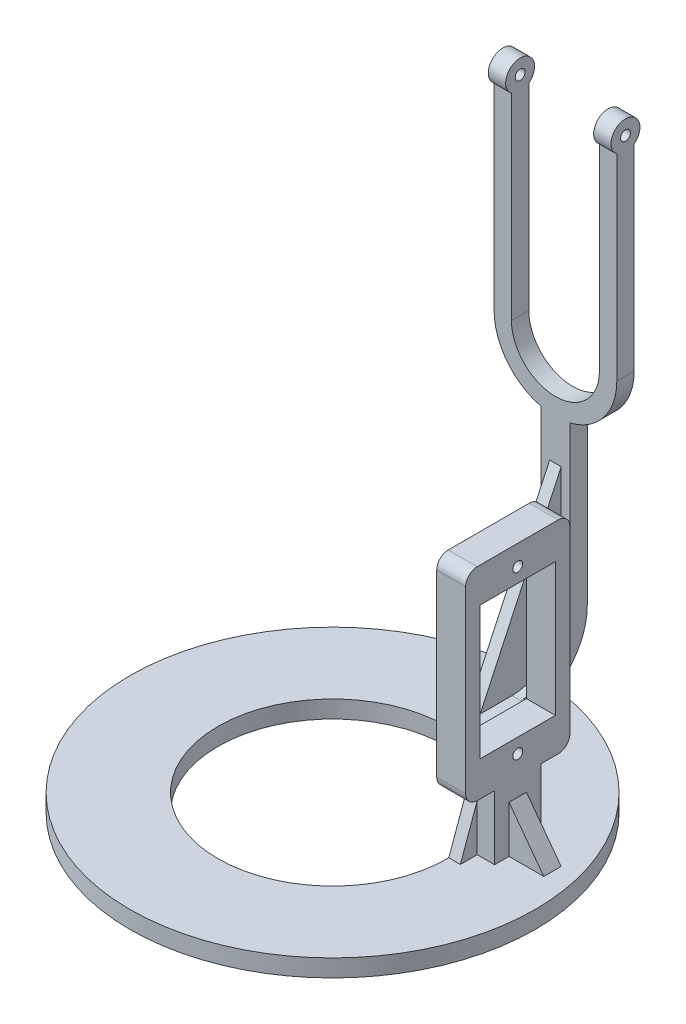
SolidWorks part; units mm, degrees
ref_plane "Plano frontal" through (0, 0, 0) normal (0, 0, 1) x (1, 0, 0)
ref_plane "Plano superior" through (0, 0, 0) normal (0, 1, 0) x (1, 0, 0)
ref_plane "Plano direito" through (0, 0, 0) normal (1, 0, 0) x (0, 0, -1)
ref_plane "Plano1" through (19.8, 0, 0) normal (1, 0, 0) x (0, 0, -1)
sketch "Esboço1" plane through (0, 0, 0) normal (1, 0, 0) x (0, 0, -1)
  circle A0 centre (0, 0) radius 2.5
  dimension "D1" = 5
extrude "Ressalto-extrusão1" add sketch "Esboço1" along normal mid plane 21.2
sketch "Esboço8" plane through (0, 0, 0) normal (0, 0, 1) x (1, 0, 0)
  line L0 (10.6, -2.5) -> (10.6, 2.5) construction
  line L1 (-10.6, 0) -> (10.6, 0)
  line L2 (-10.6, 0) -> (-10.6, -35)
  line L3 (-10.6, -35) -> (10.6, -35)
  line L4 (10.6, 0) -> (10.6, -35)
  dimension "D1" = 35
extrude "Ressalto-extrusão6" add sketch "Esboço8" along normal mid plane 3
sketch "Esboço2" plane through (0, 0, 0) normal (0, 0, 1) x (1, 0, 0)
  line L0 (-10.6, -36) -> (-10.6, -35)
  line L1 (-10.6, 2.5) -> (-10.6, -2) construction
  line L2 (-10.6, -35) -> (-7.6, -35)
  line L3 (-7.6, -35) -> (-7.6, -36)
  line L4 (7.6, -36) -> (7.6, -35)
  line L5 (7.6, -35) -> (10.6, -35)
  line L7 (10.6, -35) -> (10.6, -36)
  arc A0 (-10.6, -36) -> (10.6, -36) centre (0, -36) ccw
  arc A1 (-7.6, -36) -> (7.6, -36) centre (0, -36) ccw
  dimension "D2" = 1
  dimension "D3" = 1
  dimension "D1" = 3
extrude "Ressalto-extrusão2" add sketch "Esboço2" along normal mid plane 3
sketch "Esboço3" plane through (0, 0, 0) normal (0, 0, 1) x (1, 0, 0)
  line L0 (-7.6, -35) -> (7.6, -35) construction
  line L1 (-7.6, 2.5) -> (7.6, 2.5)
  line L2 (-7.6, 2.5) -> (-7.6, -35)
  line L3 (-7.6, -35) -> (7.6, -35)
  line L4 (7.6, 2.5) -> (7.6, -35)
  line L6 (10.6, 2.5) -> (-10.6, 2.5) construction
extrude "Corte-extrusão1" cut sketch "Esboço3" against normal through all both and the other way through all
sketch "Esboço4" plane through (0, 0, 0) normal (1, 0, 0) x (0, 0, -1)
  circle A0 centre (0, 0) radius 0.85
  dimension "D1" = 1.7
extrude "Corte-extrusão2" cut sketch "Esboço4" against normal through all both and the other way through all
sketch "Esboço5" plane through (0, 0, 0) normal (1, 0, 0) x (0, 0, -1)
  line L0 (-1.5, -36) -> (-1.5, -46.6) construction
  line L1 (-1.5, -45.1) -> (1.5, -45.1)
  line L2 (-1.5, -45.1) -> (-1.5, -75.1)
  line L3 (-1.5, -75.1) -> (1.5, -75.1)
  line L4 (1.5, -45.1) -> (1.5, -75.1)
  line L5 (1.5, -46.6) -> (1.5, -36) construction
  line L6 (-1.5, -46.6) -> (1.5, -46.6) construction
  dimension "D1" = 1.5
  dimension "D2" = 30
extrude "Ressalto-extrusão3" add sketch "Esboço5" along normal mid plane 5
sketch "Esboço6" plane through (0, 0, 0) normal (1, 0, 0) x (0, 0, -1)
  line L0 (-1.5, -75.1) -> (1.5, -75.1) construction
  line L1 (-10, -26.1517) -> (-10, -54.3785) construction
  arc A0 (0, -75.1) -> (-10, -85.1) centre (-10, -75.1) cw construction
  arc A1 (0, -75.1) -> (-10, -85.1) centre (-10, -75.1) cw construction
  arc A2 (-10, -86.6) -> (1.5, -75.1) centre (-10, -75.1) ccw
  arc A3 (-10, -83.6) -> (-1.5, -75.1) centre (-10, -75.1) ccw
  arc A4 (-10, -83.6) -> (-10, -86.6) centre (-10, -85.1) ccw
  arc A5 (1.5, -75.1) -> (-1.5, -75.1) centre (0, -75.1) ccw
  point P4 (-2.9289, -82.1711)
  dimension "D1" = 10
  dimension "D2" = 3
extrude "Ressalto-extrusão4" add sketch "Esboço6" along normal mid plane 5
sketch "Esboço7" plane through (0, 0, 0) normal (0, 1, 0) x (1, 0, 0)
  circle A0 centre (0, -40) radius 35
  dimension "D1" = 70
  dimension "D2" = 40
extrude "Ressalto-extrusão5" add sketch "Esboço7" against normal up to vertex (86.6 mm away) from vertex at -83.6 starting at point (2.5, -83.6, 10)
sketch "Esboço10" plane through (0, 0, 0) normal (1, 0, 0) x (0, 0, -1)
  line L0 (-1.5, -53.6) -> (-15.5, -83.6)
  line L1 (-5.0894, -83.6) -> (-75, -83.6) construction
  line L2 (-5.0894, -83.6) -> (-75, -83.6) construction
  line L3 (-1.5, -46.301) -> (-1.5, -75.1) construction
  line L4 (-1.5, -46.301) -> (-1.5, -75.1) construction
  point P2 (0, 0)
  point P3 (0, 0)
  dimension "D1" = 30
  dimension "D2" = 14
rib "Nervura2" sketch "Esboço10" sketch "Esboço10" thickness 2 extrusion direction parallel to sketch draft on no parameters "D1"=2
sketch "Esboço9" plane through (0, 0, 0) normal (1, 0, 0) x (0, 0, -1)
  line L0 (-92.1503, 0) -> (10.3774, 0) construction
  line L2 (-38.96, -43.85) -> (-26.66, -43.85)
  line L3 (-38.96, -43.85) -> (-38.96, -66.15)
  line L4 (-38.96, -66.15) -> (-26.66, -66.15)
  line L5 (-26.66, -43.85) -> (-26.66, -66.15)
  circle A0 centre (-32.81, -50) radius 12.7 construction
  point P9 (-32.81, -43.85)
  dimension "D1" = 25.4
  dimension "D2" = 50
  dimension "D3" = 32.81
  dimension "D4" = 22.3
  dimension "D5" = 6.15
  dimension "D6" = 12.3
sketch "Esboço11" plane through (19.8, 0, 0) normal (1, 0, 0) x (0, 0, -1)
  line L0 (-38.96, -66.15) -> (-26.66, -43.85) construction
  line L1 (-38.96, -43.85) -> (-26.66, -66.15) construction
  line L5 (-23.81, -37.5) -> (-41.81, -37.5)
  line L6 (-23.81, -37.5) -> (-23.81, -72.5)
  line L7 (-23.81, -72.5) -> (-41.81, -72.5)
  line L8 (-41.81, -37.5) -> (-41.81, -72.5)
  line L9 (-23.81, -37.5) -> (-41.81, -72.5) construction
  line L10 (-23.81, -72.5) -> (-41.81, -37.5) construction
  point P3 (-32.81, -55)
  point P4 (-32.81, -55)
  dimension "D1" = 18
  dimension "D2" = 35
extrude "Ressalto-extrusão7" add sketch "Esboço11" along normal blind 5 separate body
sketch "Esboço12" plane through (24.8, 0, 0) normal (1, 0, 0) x (0, 0, -1)
  line L0 (-38.96, -43.85) -> (-26.66, -66.15) construction
  line L2 (-39.31, -66.5) -> (-26.31, -66.5)
  line L3 (-39.31, -66.5) -> (-39.31, -43.5)
  line L4 (-39.31, -43.5) -> (-26.31, -43.5)
  line L5 (-26.31, -66.5) -> (-26.31, -43.5)
  line L6 (-39.31, -66.5) -> (-26.31, -43.5) construction
  line L7 (-39.31, -43.5) -> (-26.31, -66.5) construction
  point P4 (-32.81, -55)
  point P6 (-32.81, -55)
  dimension "D1" = 13
  dimension "D2" = 23
extrude "Corte-extrusão3" cut sketch "Esboço12" against normal through all
sketch "Esboço13" plane through (24.8, 0, 0) normal (1, 0, 0) x (0, 0, -1)
  line L0 (-23.81, -72.5) -> (-41.81, -37.5) construction
  line L1 (-32.81, -39.0473) -> (-32.81, -70.9527) construction
  circle A0 centre (-32.81, -41) radius 0.85
  circle A1 centre (-32.81, -69) radius 0.85
  point P8 (-32.81, -55)
  dimension "D1" = 1.7
  dimension "D2" = 14
  dimension "D3" = 14
extrude "Corte-extrusão4" cut sketch "Esboço13" against normal through all
sketch "Esboço14" plane through (19.8, 0, 0) normal (-1, 0, 0) x (0, 0, 1)
  line L0 (36.81, -72.5) -> (36.81, -86.6)
  line L1 (41.81, -72.5) -> (23.81, -72.5) construction
  line L2 (28.81, -86.6) -> (36.81, -86.6)
  line L4 (5, -86.6) -> (75, -86.6) construction
  line L5 (32.81, 47.9022) -> (32.81, -3.2203) construction
  line L6 (28.81, -72.5) -> (28.81, -86.6)
  line L8 (28.81, -72.5) -> (36.81, -72.5)
  circle A2 centre (32.81, -69) radius 0.85 construction
  arc A4 (28.81, -86.6) -> (26.75, -88.66) centre (26.75, -86.6) cw construction
  arc A5 (36.81, -86.6) -> (26.75, -96.66) centre (26.75, -86.6) cw construction
  point P12 (32.81, -69)
  dimension "D1" = 4
  dimension "D3" = 8
extrude "Ressalto-extrusão8" add sketch "Esboço14" against normal up to surface (5 mm away) up to face at (24.8, -69, 31.96)
fillet "Filete1" radius 2 4 edges at (22.3, -37.5, 41.81) (22.3, -72.5, 41.81) (22.3, -72.5, 23.81) (22.3, -37.5, 23.81)
sketch "Esboço15" plane through (19.8, 0, 0) normal (1, 0, 0) x (0, 0, -1)
  line L0 (-28.81, -75.5) -> (-24.81, -86.6)
  line L1 (-75, -86.6) -> (-5, -86.6) construction
  line L3 (-28.81, -72.5) -> (-28.81, -83.6) construction
  line L5 (-28.81, -72.5) -> (-25.81, -72.5) construction
  dimension "D1" = 3
  dimension "D3" = 4
rib "Nervura3" sketch "Esboço15" sketch "Esboço15" thickness 2 parameters "D1"=2
ref_plane "Plano2" through (0, 0, 32.81) normal (0, 0, 1) x (1, 0, 0)
mirror "Espelhar2" about plane through (0, 0, 32.81) normal (0, 0, 1) of "Nervura3"
sketch "Esboço16" plane through (0, -83.6, 0) normal (0, 1, 0) x (1, 0, 0)
  line L1 (19.8, -39.7289) -> (19.8, -25.8911) construction
  circle A0 centre (0, -40) radius 19.8
  circle A1 centre (0, -40) radius 35 construction
extrude "Corte-extrusão5" cut sketch "Esboço16" against normal through all
sketch "Esboço17" plane through (0, 0, 32.81) normal (0, 0, 1) x (1, 0, 0)
  line L0 (24.8, -75.5) -> (30.8, -83.6)
  line L1 (21.8, -75.5) -> (19.8, -75.5) construction
  line L3 (24.8, -72.5) -> (24.8, -83.6) construction
  line L4 (35, -83.6) -> (-35, -83.6) construction
  point P6 (0, 0)
  dimension "D1" = 6
rib "Nervura4" sketch "Esboço17" sketch "Esboço17" thickness 3 extrusion direction parallel to sketch draft on no parameters "D1"=3
